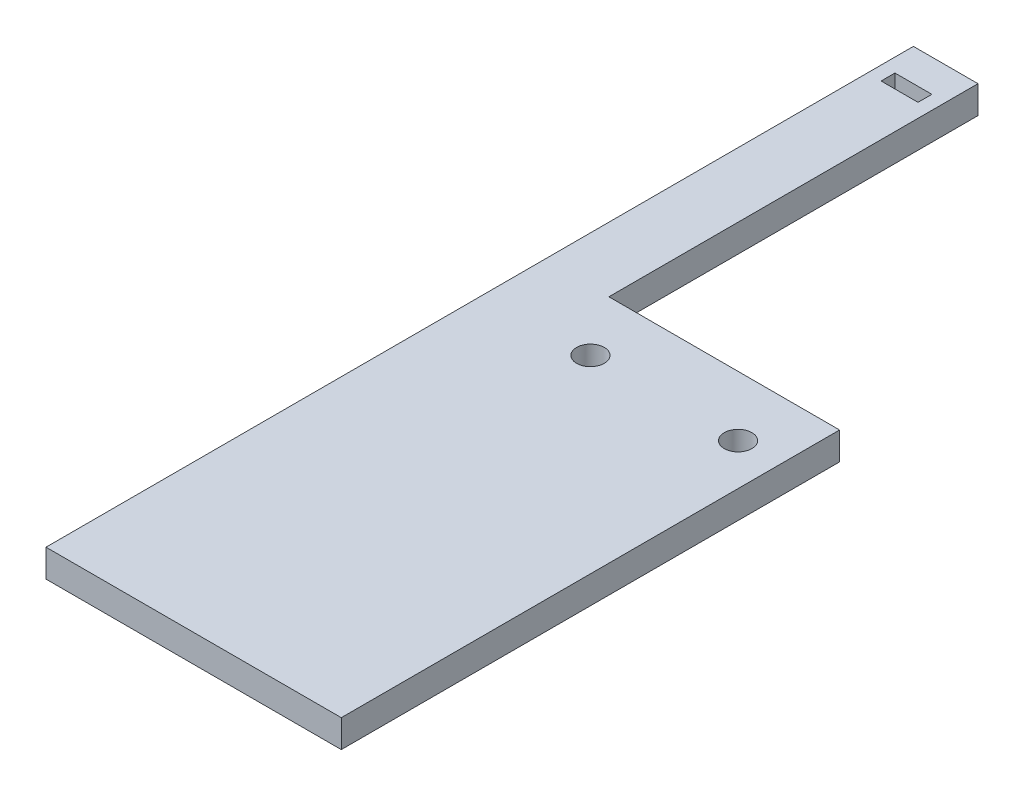
SolidWorks part; units mm, degrees
ref_plane "Front Plane" through (0, 0, 0) normal (0, 0, 1) x (1, 0, 0)
ref_plane "Top Plane" through (0, 0, 0) normal (0, 1, 0) x (1, 0, 0)
ref_plane "Right Plane" through (0, 0, 0) normal (1, 0, 0) x (0, 0, -1)
sketch "Sketch1" plane through (0, 0, 0) normal (0, 1, 0) x (1, 0, 0)
  line L0 (0, 54) -> (0, 94)
  line L1 (0, 0) -> (44, 0)
  line L2 (0, 0) -> (0, 54)
  line L4 (44, 0) -> (44, 54)
  line L5 (0, 94) -> (7, 94)
  line L9 (7, 94) -> (7, 54)
  line L10 (7, 54) -> (44, 54)
  line L12 (1.5, 90.5) -> (5.5, 90.5)
  line L13 (1.5, 90.5) -> (1.5, 89)
  line L14 (1.5, 89) -> (5.5, 89)
  line L15 (5.5, 90.5) -> (5.5, 89)
  dimension "D1" = 44
  dimension "D2" = 54
  dimension "D3" = 40
  dimension "D4" = 7
  dimension "D9" = 1.5
  dimension "D10" = 4
  dimension "D11" = 35
  dimension "D12" = 1.5
extrude "Boss-Extrude1" add sketch "Sketch1" along normal blind 3
sketch "Sketch3" plane through (0, 0, 0) normal (0, 0, 1) x (1, 0, 0)
  line L0 (0, 3) -> (44, 3) construction
  line L1 (44, 0) -> (32, 0)
  line L2 (44, 0) -> (44, 3)
  line L3 (44, 3) -> (32, 3)
  line L4 (32, 0) -> (32, 3)
  dimension "D1" = 12
extrude "Cut-Extrude2" cut sketch "Sketch3" against normal through all
sketch "Sketch5" [suppressed] plane through (0, 3, 0) normal (0, 1, 0) x (1, 0, 0)
  line L0 (44, 54) -> (12, 54) construction
  line L1 (20, 47.5) -> (36, 47.5) construction
  circle A0 centre (20, 47.5) radius 1.5
  circle A1 centre (36, 47.5) radius 1.5
  point P0 (28, 54)
  point P7 (28, 47.5)
  dimension "D1" = 3
  dimension "D2" = 3
  dimension "D3" = 16
  dimension "D4" = 6.5
sketch "Sketch6" plane through (0, 3, 0) normal (0, 1, 0) x (1, 0, 0)
  line L0 (11.5, 47.5) -> (27.5, 47.5) construction
  line L1 (32, 54) -> (7, 54) construction
  circle A0 centre (11.5, 47.5) radius 1.5
  circle A1 centre (27.5, 47.5) radius 1.5
  point P6 (19.5, 54)
  point P7 (19.5, 47.5)
  dimension "D1" = 3
  dimension "D2" = 3
  dimension "D3" = 16
  dimension "D4" = 6.5
extrude "Cut-Extrude3" [suppressed] cut sketch "Sketch5" against normal blind 10
extrude "Cut-Extrude4" cut sketch "Sketch6" against normal blind 10
